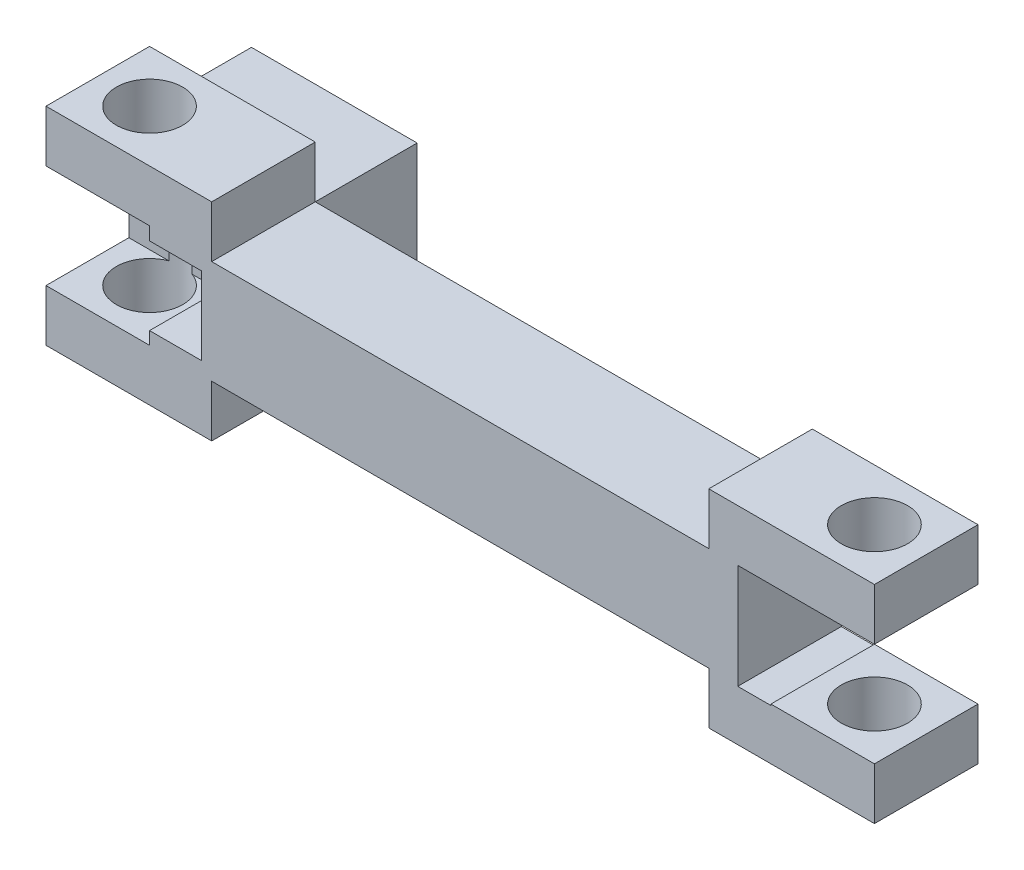
SolidWorks part; units mm, degrees
ref_plane "Front Plane" through (0, 0, 0) normal (0, 0, 1) x (1, 0, 0)
ref_plane "Top Plane" through (0, 0, 0) normal (0, 1, 0) x (1, 0, 0)
ref_plane "Right Plane" through (0, 0, 0) normal (1, 0, 0) x (0, 0, -1)
sketch "Sketch1" plane through (0, 0, 0) normal (0, 0, 1) x (1, 0, 0)
  line L0 (-60.8, 45) -> (-60.8, 57.5)
  line L1 (-60.8, 45) -> (59.2, 45)
  line L2 (-100.8, 45) -> (-100.8, 20)
  line L3 (-60.8, 20) -> (59.2, 20)
  line L5 (-100.8, 7.5) -> (-60.8, 7.5)
  line L6 (-100.8, 7.5) -> (-100.8, 57.5)
  line L7 (-100.8, 57.5) -> (-60.8, 57.5)
  line L8 (-60.8, 7.5) -> (-60.8, 20)
  line L9 (74.2, 20) -> (74.2, 45)
  line L10 (59.2, 57.5) -> (99.2, 57.5)
  line L11 (59.2, 57.5) -> (59.2, 45)
  line L12 (59.2, 7.5) -> (99.2, 7.5)
  line L13 (99.2, 57.5) -> (99.2, 45)
  line L14 (59.2, 20) -> (59.2, 7.5)
  line L15 (74.2, 45) -> (99.2, 45)
  line L16 (74.2, 20) -> (99.2, 20)
  line L17 (99.2, 20) -> (99.2, 7.5)
  dimension "D1" = 200
  dimension "D2" = 25
  dimension "D3" = 40
  dimension "D4" = 50
  dimension "D5" = 50
  dimension "D6" = 40
  dimension "D7" = 200
extrude "Boss-Extrude1" add sketch "Sketch1" along normal blind 25 contours L17 L16 L9 L15 L13 L10 L11 L1 L0 L7 L6 L2 L5 L8 L3 L14 L12
sketch "Sketch2" plane through (0, 57.5, 0) normal (0, 1, 0) x (1, 0, 0)
  line L0 (-100.8, 0) -> (-60.8, 0) construction
  line L2 (-100.8, -25) -> (-100.8, 0) construction
  circle A0 centre (-88.3, -12.5) radius 8
  dimension "D1" = 16
  dimension "D2" = 12.5
  dimension "D3" = 12.5
extrude "Cut-Extrude1" cut sketch "Sketch2" against normal blind 70.5
sketch "Sketch3" plane through (0, 57.5, 0) normal (0, 1, 0) x (1, 0, 0)
  line L0 (99.2, -25) -> (99.2, 0) construction
  line L1 (59.2, 0) -> (99.2, 0) construction
  circle A0 centre (86.7, -12.5) radius 8
  dimension "D1" = 16
  dimension "D2" = 12.5
  dimension "D3" = 12.5
extrude "Cut-Extrude2" cut sketch "Sketch3" against normal blind 88
sketch "Sketch4" plane through (0, 0, 0) normal (0, 0, -1) x (-1, 0, 0)
  line L0 (100.8, 7.5) -> (100.8, 57.5) construction
  line L1 (60.8, 45) -> (100.8, 45)
  line L2 (60.8, 45) -> (60.8, 20)
  line L3 (60.8, 20) -> (100.8, 20)
  line L4 (100.8, 45) -> (100.8, 20)
  line L5 (60.8, 20) -> (-59.2, 20) construction
  dimension "D1" = 0
extrude "Boss-Extrude2" add sketch "Sketch4" along normal blind 24.6
sketch "Sketch5" plane through (0, 0, -24.6) normal (0, 0, -1) x (-1, 0, 0)
  line L0 (100.8, 45) -> (60.8, 45) construction
  line L1 (100.8, 20) -> (100.8, 45) construction
  circle A0 centre (85.8, 32.5) radius 7.5
  dimension "D1" = 15
  dimension "D2" = 12.5
  dimension "D3" = 15
extrude "Cut-Extrude4" cut sketch "Sketch5" against normal blind 4.5
sketch "Sketch7" plane through (0, 0, 25) normal (0, 0, 1) x (1, 0, 0)
  line L1 (-75.8, 20) -> (-100.8, 20)
  line L2 (-75.8, 20) -> (-75.8, 45)
  line L3 (-75.8, 45) -> (-100.8, 45)
  line L4 (-100.8, 20) -> (-100.8, 45)
  dimension "D1" = 25
  dimension "D2" = 25
extrude "Cut-Extrude6" cut sketch "Sketch7" against normal blind 20
sketch "Sketch8" plane through (0, 7.5, 0) normal (0, -1, 0) x (1, 0, 0)
  line L0 (-88.3, 12.5) -> (-100.8, 12.5) construction
  line L1 (-100.8, 25) -> (-100.8, 0) construction
sketch "Sketch9" plane through (-100.8, 0, 0) normal (-1, 0, 0) x (0, 0, 1)
  line L0 (12.5, 7.5) -> (12.5, 20) construction
  line L1 (25, 7.5) -> (0, 7.5) construction
  line L2 (5, 20) -> (25, 20) construction
sketch "Sketch10" plane through (-100.8, 0, 0) normal (-1, 0, 0) x (0, 0, 1)
  line L0 (-24.6, 32.5) -> (25.1891, 32.5) construction
  line L1 (-24.6, 20) -> (-24.6, 45) construction
  line L2 (12.5, 20) -> (12.5, 45) construction
  line L3 (5, 45) -> (25, 45) construction
  line L5 (12.5, 38.75) -> (-12.5, 38.75)
  line L6 (12.5, 38.75) -> (12.5, 26.25)
  line L7 (12.5, 26.25) -> (-12.5, 26.25)
  line L8 (-12.5, 38.75) -> (-12.5, 26.25)
  dimension "D1" = 12.5
  dimension "D2" = 25
extrude "Cut-Extrude7" cut sketch "Sketch10" against normal blind 25
sketch "Sketch11" plane through (0, 57.5, 0) normal (0, 1, 0) x (1, 0, 0)
  line L0 (-88.3, -12.5) -> (-88.3, -25) construction
  line L1 (-100.8, -25) -> (-60.8, -25) construction
sketch "Sketch12" plane through (0, 0, 25) normal (0, 0, 1) x (1, 0, 0)
  line L0 (-88.2936, 57.4113) -> (-88.3, 7.5) construction
  line L1 (-88.3, 7.5) -> (-100.8, 7.5) construction
  line L2 (-100.8, 7.5) -> (-60.8, 7.5) construction
sketch "Sketch13" plane through (0, 0, 25) normal (0, 0, 1) x (1, 0, 0)
  line L0 (-88.2968, 41.8307) -> (-88.2968, 23.0807)
  line L1 (-88.2968, 41.8307) -> (-63.2968, 41.8307)
  line L2 (-88.2968, 23.0807) -> (-63.2968, 23.0807)
  line L3 (-63.2968, 41.8307) -> (-63.2968, 23.0807)
  line L6 (-88.2936, 57.4113) -> (-88.3, 7.5)
  line M24 (-75.8, 45) -> (-75.8, 20)
  dimension "D1" = 25
extrude "Cut-Extrude9" cut sketch "Sketch13" against normal blind 25 contours L1 L6 L0 L2 M24 | L3 L1 L2 M24
sketch "Sketch17" plane through (74.2, 0, 0) normal (1, 0, 0) x (0, 0, -1)
  line L0 (-25, 45) -> (0, 45)
  line L1 (-25, 45) -> (-25, 19.7003)
  line L2 (0, 45) -> (0, 19.7003)
  line L3 (-25, 19.7003) -> (0, 19.7003)
extrude "Cut-Extrude11" cut sketch "Sketch17" against normal blind 8
